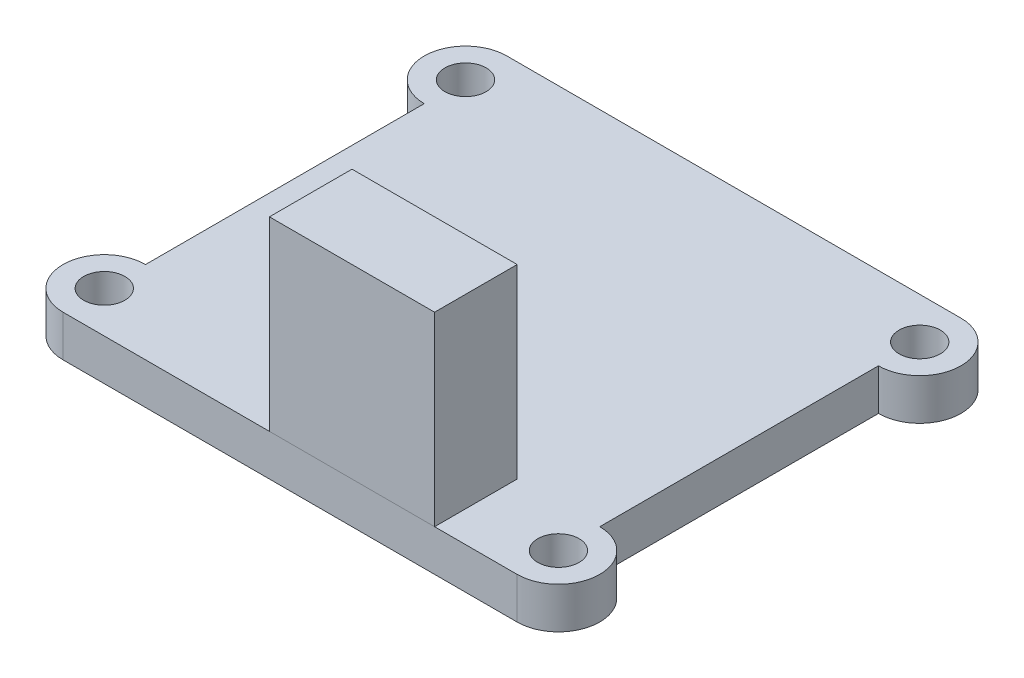
SolidWorks part; units mm, degrees
material "电源线路板"
ref_plane "前视基准面" through (0, 0, 0) normal (0, 0, 1) x (1, 0, 0)
ref_plane "上视基准面" through (0, 0, 0) normal (0, 1, 0) x (1, 0, 0)
ref_plane "右视基准面" through (0, 0, 0) normal (1, 0, 0) x (0, 0, -1)
other "Configuration Table"
sketch "草图1" plane through (0, 0, 0) normal (0, 1, 0) x (1, 0, 0)
  line L0 (-19.8415, 0) -> (33.166, 0) construction
  line L1 (-11, -10.75) -> (11, -10.75)
  line L2 (-11, -6.75) -> (-11, 6.75)
  line L3 (-11, 10.75) -> (11, 10.75)
  line L4 (11, -6.75) -> (11, 6.75)
  line L5 (-11, -10.75) -> (0, 0) construction
  line L6 (-11, 10.75) -> (11, -10.75) construction
  line L7 (0, 18.4094) -> (0, -21.1075) construction
  arc A0 (-11, 10.75) -> (-11, 6.75) centre (-11, 8.75) ccw
  arc A1 (11, 10.75) -> (11, 6.75) centre (11, 8.75) cw
  arc A2 (11, -10.75) -> (11, -6.75) centre (11, -8.75) ccw
  arc A3 (-11, -10.75) -> (-11, -6.75) centre (-11, -8.75) cw
  circle A4 centre (-11, 8.75) radius 1
  circle A5 centre (11, 8.75) radius 1
  circle A6 centre (11, -8.75) radius 1
  circle A7 centre (-11, -8.75) radius 1
  point P0 (0, 0)
  dimension "D3" = 2
  dimension "D4" = 2
  dimension "D1" = 22
  dimension "D2" = 21.5
extrude "凸台-拉伸1" add sketch "草图1" along normal blind 2
sketch "草图2" plane through (0, 2, 0) normal (0, 1, 0) x (1, 0, 0)
  line L1 (-1, -10.75) -> (7, -10.75)
  line L2 (-1, -10.75) -> (-1, -6.75)
  line L3 (-1, -6.75) -> (7, -6.75)
  line L4 (11, 10.75) -> (-11, 10.75)
  line L5 (-11, 6.75) -> (-11, -6.75)
  line L6 (-11, -10.75) -> (11, -10.75)
  line L7 (11, -6.75) -> (11, 6.75)
  line L8 (11, 10.75) -> (-11, 10.75) construction
  line L9 (-11, 6.75) -> (-11, -6.75) construction
  line L10 (-11, -10.75) -> (11, -10.75) construction
  line L11 (11, -6.75) -> (11, 6.75) construction
  line L12 (7, -10.75) -> (7, -6.75)
  arc A4 (11, 6.75) -> (11, 10.75) centre (11, 8.75) ccw
  arc A5 (-11, 10.75) -> (-11, 6.75) centre (-11, 8.75) ccw
  arc A6 (-11, -6.75) -> (-11, -10.75) centre (-11, -8.75) ccw
  arc A7 (11, -10.75) -> (11, -6.75) centre (11, -8.75) ccw
  arc A8 (11, 6.75) -> (11, 10.75) centre (11, 8.75) ccw construction
  arc A9 (-11, 10.75) -> (-11, 6.75) centre (-11, 8.75) ccw construction
  arc A10 (-11, -6.75) -> (-11, -10.75) centre (-11, -8.75) ccw construction
  arc A11 (11, -10.75) -> (11, -6.75) centre (11, -8.75) ccw construction
  dimension "D2" = 4
  dimension "D3" = 8
  dimension "D4" = 4
  dimension "D1" = 0
extrude "凸台-拉伸2" add sketch "草图2" along normal blind 9 separate body
